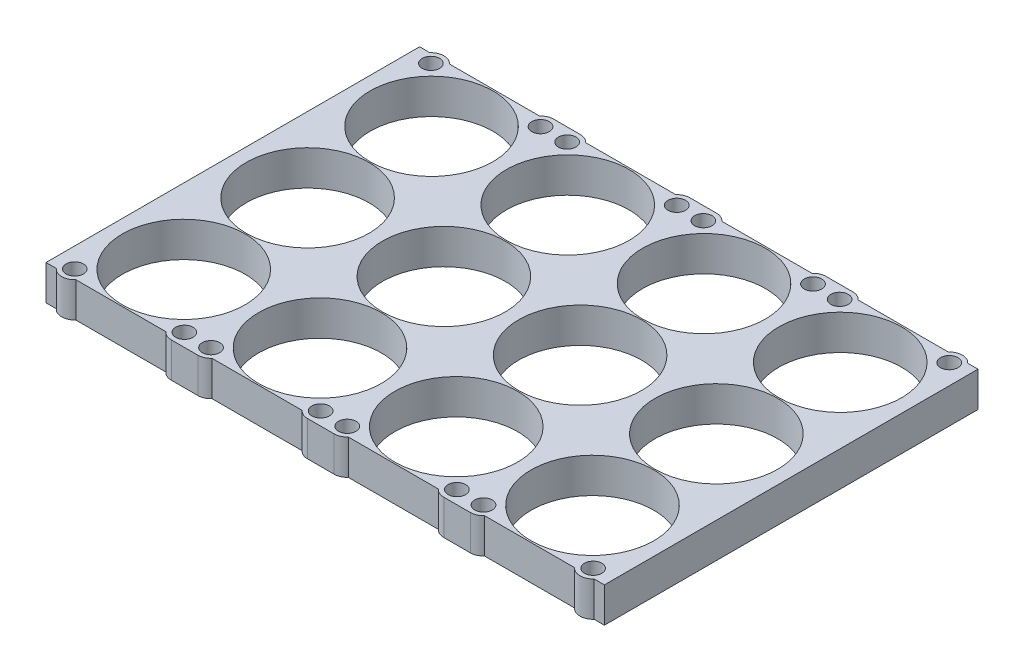
SolidWorks part; units mm, degrees
ref_plane "Front Plane" through (0, 0, 0) normal (0, 0, 1) x (1, 0, 0)
ref_plane "Top Plane" through (0, 0, 0) normal (0, 1, 0) x (1, 0, 0)
ref_plane "Right Plane" through (0, 0, 0) normal (1, 0, 0) x (0, 0, -1)
sketch "Sketch1" plane through (0, 0, 0) normal (0, 1, 0) x (1, 0, 0)
  line L0 (11.122, -9.411) -> (11.122, -19.379)
  line L1 (0, 0) -> (127.76, 0)
  line L2 (0, 0) -> (0, -85.48)
  line L3 (0, -85.48) -> (127.76, -85.48)
  line L4 (127.76, 0) -> (127.76, -85.48)
  line L5 (23.122, -9.411) -> (23.122, -19.379)
  line L6 (42.294, -9.411) -> (42.294, -19.379)
  line L7 (54.294, -9.411) -> (54.294, -19.379)
  line L8 (73.466, -9.411) -> (73.466, -19.379)
  line L9 (85.466, -9.411) -> (85.466, -19.379)
  line L10 (104.638, -9.411) -> (104.638, -19.379)
  line L11 (116.638, -9.411) -> (116.638, -19.379)
  line L12 (42.294, -37.756) -> (42.294, -47.724)
  line L13 (54.294, -37.756) -> (54.294, -47.724)
  line L14 (73.466, -37.756) -> (73.466, -47.724)
  line L15 (85.466, -37.756) -> (85.466, -47.724)
  line L16 (104.638, -37.756) -> (104.638, -47.724)
  line L17 (116.638, -37.756) -> (116.638, -47.724)
  line L18 (42.294, -66.101) -> (42.294, -76.069)
  line L19 (54.294, -66.101) -> (54.294, -76.069)
  line L20 (73.466, -66.101) -> (73.466, -76.069)
  line L21 (85.466, -66.101) -> (85.466, -76.069)
  line L22 (104.638, -66.101) -> (104.638, -76.069)
  line L23 (116.638, -66.101) -> (116.638, -76.069)
  line L24 (11.122, -37.756) -> (11.122, -47.724)
  line L25 (23.122, -37.756) -> (23.122, -47.724)
  line L26 (11.122, -66.101) -> (11.122, -76.069)
  line L27 (23.122, -66.101) -> (23.122, -76.069)
  circle A2 centre (17.122, -14.395) radius 14.05
  circle A12 centre (48.294, -14.395) radius 14.05
  circle A13 centre (79.466, -14.395) radius 14.05
  circle A14 centre (110.638, -14.395) radius 14.05
  circle A15 centre (48.294, -42.74) radius 14.05
  circle A16 centre (79.466, -42.74) radius 14.05
  circle A17 centre (110.638, -42.74) radius 14.05
  circle A18 centre (48.294, -71.085) radius 14.05
  circle A19 centre (79.466, -71.085) radius 14.05
  circle A20 centre (110.638, -71.085) radius 14.05
  circle A21 centre (17.122, -42.74) radius 14.05
  circle A22 centre (17.122, -71.085) radius 14.05
  arc A23 (11.122, -19.379) -> (23.122, -19.379) centre (17.122, -14.395) ccw
  arc A24 (23.122, -9.411) -> (11.122, -9.411) centre (17.122, -14.395) ccw
  arc A25 (42.294, -19.379) -> (54.294, -19.379) centre (48.294, -14.395) ccw
  arc A26 (54.294, -9.411) -> (42.294, -9.411) centre (48.294, -14.395) ccw
  arc A27 (73.466, -19.379) -> (85.466, -19.379) centre (79.466, -14.395) ccw
  arc A28 (85.466, -9.411) -> (73.466, -9.411) centre (79.466, -14.395) ccw
  arc A29 (104.638, -19.379) -> (116.638, -19.379) centre (110.638, -14.395) ccw
  arc A30 (116.638, -9.411) -> (104.638, -9.411) centre (110.638, -14.395) ccw
  arc A31 (42.294, -47.724) -> (54.294, -47.724) centre (48.294, -42.74) ccw
  arc A32 (54.294, -37.756) -> (42.294, -37.756) centre (48.294, -42.74) ccw
  arc A33 (73.466, -47.724) -> (85.466, -47.724) centre (79.466, -42.74) ccw
  arc A34 (85.466, -37.756) -> (73.466, -37.756) centre (79.466, -42.74) ccw
  arc A35 (104.638, -47.724) -> (116.638, -47.724) centre (110.638, -42.74) ccw
  arc A36 (116.638, -37.756) -> (104.638, -37.756) centre (110.638, -42.74) ccw
  arc A37 (42.294, -76.069) -> (54.294, -76.069) centre (48.294, -71.085) ccw
  arc A38 (54.294, -66.101) -> (42.294, -66.101) centre (48.294, -71.085) ccw
  arc A39 (73.466, -76.069) -> (85.466, -76.069) centre (79.466, -71.085) ccw
  arc A40 (85.466, -66.101) -> (73.466, -66.101) centre (79.466, -71.085) ccw
  arc A41 (104.638, -76.069) -> (116.638, -76.069) centre (110.638, -71.085) ccw
  arc A42 (116.638, -66.101) -> (104.638, -66.101) centre (110.638, -71.085) ccw
  arc A43 (11.122, -47.724) -> (23.122, -47.724) centre (17.122, -42.74) ccw
  arc A44 (23.122, -37.756) -> (11.122, -37.756) centre (17.122, -42.74) ccw
  arc A45 (11.122, -76.069) -> (23.122, -76.069) centre (17.122, -71.085) ccw
  arc A46 (23.122, -66.101) -> (11.122, -66.101) centre (17.122, -71.085) ccw
  dimension "D3" = 4
  dimension "D4" = 14.395
  dimension "D9" = 15.6
  dimension "D11" = 28.1
  dimension "D1" = 127.76
  dimension "D2" = 85.48
  dimension "D5" = 3
  dimension "D6" = 14.395
  dimension "D7" = 17.122
  dimension "D8" = 17.122
  dimension "D10" = 12
  dimension "D12" = 4
  dimension "D13" = 3
extrude "Boss-Extrude3" add sketch "Sketch1" along normal blind 8 contours L4 L1 L2 L3 A22 A21 A20 A19 A18 A17 A16 A15 A14 A13 A12 A2
sketch "Sketch2" plane through (0, 0, 0) normal (0, -1, 0) x (1, 0, 0)
  line L0 (0, 0) -> (127.76, 0) construction
  line L1 (0, 85.48) -> (127.76, 85.48) construction
  line L2 (4.582, 2) -> (29.662, 2) construction
  line L3 (4.582, 83.48) -> (29.662, 83.48) construction
  line L4 (17.122, 83.48) -> (17.122, 2) construction
  line L5 (35.754, 2) -> (60.834, 2) construction
  line L6 (35.754, 83.48) -> (60.834, 83.48) construction
  line L7 (48.294, 83.48) -> (48.294, 2) construction
  line L8 (66.926, 2) -> (92.006, 2) construction
  line L9 (66.926, 83.48) -> (92.006, 83.48) construction
  line L10 (79.466, 83.48) -> (79.466, 2) construction
  line L11 (98.098, 2) -> (123.178, 2) construction
  line L12 (98.098, 83.48) -> (123.178, 83.48) construction
  line L13 (110.638, 83.48) -> (110.638, 2) construction
  line L14 (3.072, 42.74) -> (31.172, 42.74) construction
  line L15 (96.588, 42.74) -> (124.688, 42.74) construction
  line L17 (29.662, 5) -> (35.754, 5)
  line L18 (29.662, 5) -> (29.662, -1)
  line L19 (29.662, -1) -> (35.754, -1)
  line L20 (35.754, 5) -> (35.754, -1)
  line L21 (60.834, 5) -> (66.926, 5)
  line L22 (60.834, 5) -> (60.834, -1)
  line L23 (60.834, -1) -> (66.926, -1)
  line L24 (66.926, 5) -> (66.926, -1)
  line L25 (92.006, 5) -> (98.098, 5)
  line L26 (92.006, 5) -> (92.006, -1)
  line L27 (92.006, -1) -> (98.098, -1)
  line L28 (98.098, 5) -> (98.098, -1)
  line L29 (92.006, 86.48) -> (98.098, 86.48)
  line L30 (92.006, 86.48) -> (92.006, 80.48)
  line L31 (92.006, 80.48) -> (98.098, 80.48)
  line L32 (98.098, 86.48) -> (98.098, 80.48)
  line L33 (66.926, 86.48) -> (60.834, 86.48)
  line L34 (66.926, 86.48) -> (66.926, 80.48)
  line L35 (66.926, 80.48) -> (60.834, 80.48)
  line L36 (60.834, 86.48) -> (60.834, 80.48)
  line L37 (29.662, 86.48) -> (35.754, 86.48)
  line L38 (29.662, 86.48) -> (29.662, 80.48)
  line L39 (29.662, 80.48) -> (35.754, 80.48)
  line L40 (35.754, 86.48) -> (35.754, 80.48)
  circle A0 centre (4.582, 2) radius 3
  circle A1 centre (29.662, 2) radius 3
  circle A2 centre (29.662, 83.48) radius 3
  circle A3 centre (4.582, 83.48) radius 3
  circle A4 centre (35.754, 2) radius 3
  circle A5 centre (60.834, 2) radius 3
  circle A6 centre (60.834, 83.48) radius 3
  circle A7 centre (35.754, 83.48) radius 3
  circle A8 centre (66.926, 2) radius 3
  circle A9 centre (92.006, 2) radius 3
  circle A10 centre (92.006, 83.48) radius 3
  circle A11 centre (66.926, 83.48) radius 3
  circle A12 centre (98.098, 2) radius 3
  circle A13 centre (123.178, 2) radius 3
  circle A14 centre (123.178, 83.48) radius 3
  circle A15 centre (98.098, 83.48) radius 3
  circle A16 centre (17.122, 42.74) radius 14.05 construction
  circle A17 centre (110.638, 42.74) radius 14.05 construction
  point P49 (110.638, 42.74)
  point P56 (17.122, 42.74)
  point P80 (29.662, 5)
  point P81 (35.754, 5)
  point P82 (35.754, 86.48)
  point P83 (29.662, 80.48)
  point P84 (35.754, 86.48)
  point P85 (35.754, 80.48)
  point P86 (0, 0)
  point P87 (0, 0)
  point P88 (0, 0)
  point P89 (0, 0)
  point P90 (0, 0)
  point P91 (0, 0)
  point P92 (0, 0)
  point P93 (0, 0)
  line M15 (127.76, 85.48) -> (0, 85.48)
  line M17 (0, 0) -> (127.76, 0)
  dimension "D1" = 6
  dimension "D2" = 2
  dimension "D5" = 25.08
  dimension "D6" = 2
  dimension "D3" = 2
  dimension "D4" = 2
  dimension "D7" = 4
extrude "Boss-Extrude4" add sketch "Sketch2" against normal up to surface (8 mm away) contours A0 M17 | A1 L18 M17 | L18 A1 M17 | A4 A1 L19 M17 | A4 L20 M17 | L20 A4 M17 | A5 L22 M17 | L22 A5 M17 | A8 A5 L23 M17 | A8 L24 M17 | L24 A8 M17 | A9 L26 M17 | L26 A9 M17 | A12 A9 L27 M17 | A12 L28 M17 | L28 A12 M17 | A13 M17 | A14 M15 | A15 L32 M15 | L32 A15 M15 | A15 L29 A10 M15 | A10 L30 M15 | L30 A10 M15 | A11 L34 M15 | L34 A11 M15 | A11 L33 A6 M15 | A6 L36 M15 | L36 A6 M15 | A3 M15 | L38 A2 M15 | A2 L38 M15 | A7 L37 A2 M15 | L40 A7 M15 | A7 L40 M15 up to face at (17.122, 8, 85.135)
sketch "Sketch4" plane through (0, 8, 0) normal (0, 1, 0) x (1, 0, 0)
  circle A0 centre (4.582, -83.48) radius 1.1
  circle A1 centre (29.662, -83.48) radius 1.1
  circle A2 centre (29.662, -2) radius 1.1
  circle A3 centre (4.582, -2) radius 1.1
  circle A4 centre (35.754, -83.48) radius 1.1
  circle A5 centre (60.834, -83.48) radius 1.1
  circle A6 centre (60.834, -2) radius 1.1
  circle A7 centre (35.754, -2) radius 1.1
  circle A8 centre (66.926, -83.48) radius 1.1
  circle A9 centre (92.006, -83.48) radius 1.1
  circle A10 centre (92.006, -2) radius 1.1
  circle A11 centre (66.926, -2) radius 1.1
  circle A12 centre (98.098, -83.48) radius 1.1
  circle A13 centre (123.178, -83.48) radius 1.1
  circle A14 centre (123.178, -2) radius 1.1
  circle A15 centre (98.098, -2) radius 1.1
  point P3 (0, 0)
  point P5 (92.097, -83.48)
  point P38 (92.423, -83.48)
  dimension "D1" = 2.2
  dimension "D2" = 2
  dimension "D3" = 2
extrude "Cut-Extrude2" cut sketch "Sketch4" against normal blind 10
sketch "Sketch7" plane through (0, 0, 0) normal (0, 1, 0) x (1, 0, 0)
  circle A0 centre (4.582, -83.48) radius 2
  circle A1 centre (29.662, -83.48) radius 2
  circle A2 centre (29.662, -2) radius 2
  circle A3 centre (4.582, -2) radius 2
  circle A4 centre (35.754, -83.48) radius 2
  circle A5 centre (60.834, -83.48) radius 2
  circle A6 centre (60.834, -2) radius 2
  circle A7 centre (35.754, -2) radius 2
  circle A8 centre (66.926, -83.48) radius 2
  circle A9 centre (92.006, -83.48) radius 2
  circle A10 centre (92.006, -2) radius 2
  circle A11 centre (66.926, -2) radius 2
  circle A12 centre (98.098, -83.48) radius 2
  circle A13 centre (123.178, -83.48) radius 2
  circle A14 centre (123.178, -2) radius 2
  circle A15 centre (98.098, -2) radius 2
  point P3 (0, 0)
  point P5 (92.097, -83.48)
  point P12 (65.6416, -82.8995)
  point P38 (92.423, -83.48)
  point P40 (68.1256, -88.6618)
  point P41 (0, 0)
  point P43 (122.1829, -92.8522)
  point P45 (100.0491, -83.48)
  point P47 (92.6113, -83.48)
  point P49 (98.098, -2)
  dimension "D1" = 4
  dimension "D2" = 2
  dimension "D3" = 2
  dimension "D4" = 4
extrude "Cut-Extrude3" cut sketch "Sketch7" against normal blind 3 from surface at 8 starting at face at (60.834, 8, 84.58)
